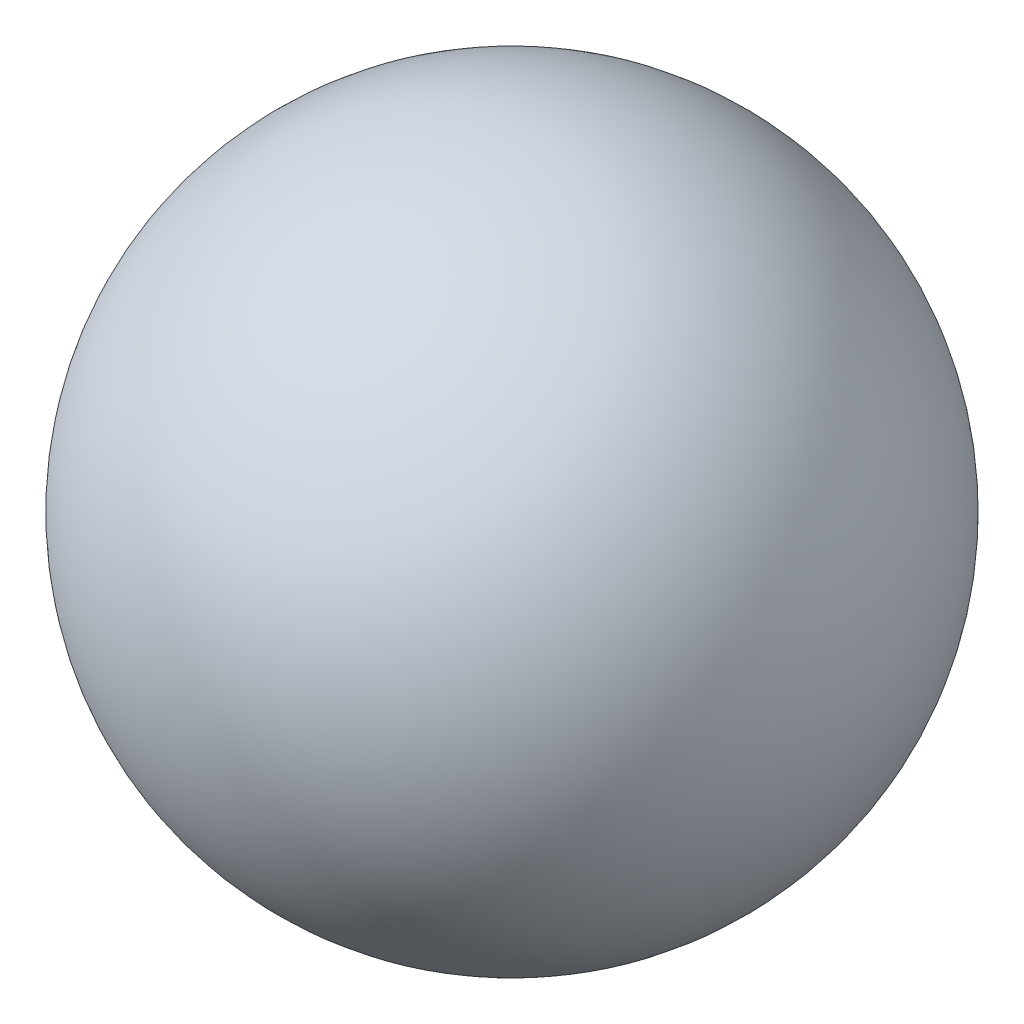
SolidWorks part; units mm, degrees
ref_plane "前视基准面" through (0, 0, 0) normal (0, 0, 1) x (1, 0, 0)
ref_plane "上视基准面" through (0, 0, 0) normal (0, 1, 0) x (1, 0, 0)
ref_plane "右视基准面" through (0, 0, 0) normal (1, 0, 0) x (0, 0, -1)
sketch "草图1" plane through (0, 0, 0) normal (0, 0, 1) x (1, 0, 0)
  line L0 (0, 0) -> (0, 12)
  line L1 (0, 12) -> (0, 0)
  line L2 (0, -12) -> (0, 0)
  arc A0 (0, 12) -> (0, -12) centre (0, 0) cw
  dimension "D1" = 12
  dimension "D2" = 12
revolve "旋转1" add sketch "草图1" angle 360 about L2
